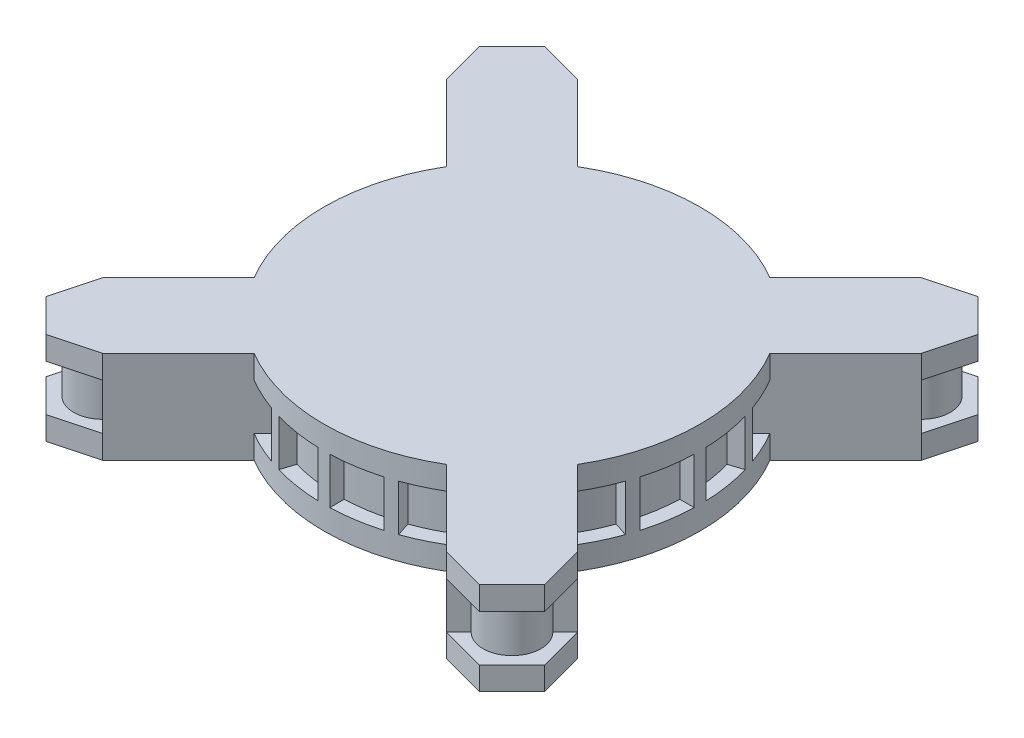
SolidWorks part; units mm, degrees
ref_plane "Front Plane" through (0, 0, 0) normal (0, 0, 1) x (1, 0, 0)
ref_plane "Top Plane" through (0, 0, 0) normal (0, 1, 0) x (1, 0, 0)
ref_plane "Right Plane" through (0, 0, 0) normal (1, 0, 0) x (0, 0, -1)
ref_plane "Plane3" through (0, 4, 0) normal (0, 1, 0) x (1, 0, 0)
ref_plane "Plane4" through (0, 12, 0) normal (0, 1, 0) x (1, 0, 0)
ref_plane "Plane5" through (0, 16, 0) normal (0, 1, 0) x (1, 0, 0)
sketch "Sketch11" plane through (0, 0, 0) normal (0, 1, 0) x (1, 0, 0)
  line L0 (27.9307, -16.617) -> (41.0122, -29.6985)
  line L1 (27.9307, 16.617) -> (41.0122, 29.6985)
  line L2 (16.617, 27.9307) -> (29.6985, 41.0122)
  line L3 (16.617, -27.9307) -> (29.6985, -41.0122)
  line L4 (-16.617, -27.9307) -> (-29.6985, -41.0122)
  line L5 (-27.9307, -16.617) -> (-41.0122, -29.6985)
  line L6 (-27.9307, 16.617) -> (-41.0122, 29.6985)
  line L7 (-16.617, 27.9307) -> (-29.6985, 41.0122)
  line L8 (43.0827, -37.4259) -> (41.0122, -29.6985)
  line L9 (37.4259, -43.0827) -> (43.0827, -37.4259)
  line L13 (41.0122, 29.6985) -> (43.0827, 37.4259)
  line L14 (43.0827, 37.4259) -> (37.4259, 43.0827)
  line L15 (37.4259, 43.0827) -> (29.6985, 41.0122)
  line L16 (30.4564, 30.4564) -> (33.2848, 27.6279) [skipped]
  line L17 (28.6632, 37.1485) -> (27.6279, 33.2848) [skipped]
  line L18 (37.1485, 28.6632) -> (41.0122, 29.6985) [skipped]
  line L19 (29.6985, -41.0122) -> (37.4259, -43.0827)
  line L20 (-37.4259, -43.0827) -> (-29.6985, -41.0122)
  line L21 (-43.0827, -37.4259) -> (-37.4259, -43.0827)
  line L22 (-41.0122, -29.6985) -> (-43.0827, -37.4259)
  line L23 (-43.0827, 37.4259) -> (-41.0122, 29.6985)
  line L24 (-37.4259, 43.0827) -> (-43.0827, 37.4259)
  line L25 (-29.6985, 41.0122) -> (-37.4259, 43.0827)
  arc A0 (16.617, 27.9307) -> (-16.617, 27.9307) centre (0, 0) ccw
  arc A1 (-27.9307, 16.617) -> (-27.9307, -16.617) centre (0, 0) ccw
  arc A2 (-16.617, -27.9307) -> (16.617, -27.9307) centre (0, 0) ccw
  arc A3 (27.9307, -16.617) -> (27.9307, 16.617) centre (0, 0) ccw
  point P23 (0, 0)
  point P46 (0, 0)
extrude "Boss-Extrude8" add sketch "Sketch11" along normal blind 4
sketch "Sketch12" plane through (0, 4, 0) normal (0, 1, 0) x (1, 0, 0)
  line L0 (38.8909, 31.8198) -> (41.0122, 29.6985)
  line L2 (26.1019, 14.7882) -> (41.0122, 29.6985)
  line L3 (14.7882, 26.1019) -> (29.6985, 41.0122)
  line L4 (29.6985, 41.0122) -> (31.8198, 38.8909)
  line L5 (26.1019, -14.7882) -> (41.0122, -29.6985)
  line L6 (41.0122, -29.6985) -> (38.8909, -31.8198)
  line L7 (31.8198, -38.8909) -> (29.6985, -41.0122)
  line L8 (14.7882, -26.1019) -> (29.6985, -41.0122)
  line L9 (-14.7882, -26.1019) -> (-29.6985, -41.0122)
  line L10 (-29.6985, -41.0122) -> (-31.8198, -38.8909)
  line L11 (-38.8909, -31.8198) -> (-41.0122, -29.6985)
  line L12 (-26.1019, -14.7882) -> (-41.0122, -29.6985)
  line L13 (-26.1019, 14.7882) -> (-41.0122, 29.6985)
  line L14 (-41.0122, 29.6985) -> (-38.8909, 31.8198)
  line L15 (-31.8198, 38.8909) -> (-29.6985, 41.0122)
  line L16 (-14.7882, 26.1019) -> (-29.6985, 41.0122)
  line L17 (-1, 32.4846) -> (-1, 29.9833)
  line L18 (10.9894, 30.5857) -> (10.2164, 28.2068)
  line L19 (1, 32.4846) -> (1, 29.9833)
  line L20 (9.0872, 31.2037) -> (8.3143, 28.8249)
  line L25 (31.2037, 9.0872) -> (28.8249, 8.3143)
  line L26 (30.5857, 10.9894) -> (28.2068, 10.2164)
  line L27 (32.4846, -1) -> (29.9833, -1)
  line L28 (32.4846, 1) -> (29.9833, 1)
  line L29 (30.5857, -10.9894) -> (28.2068, -10.2164)
  line L30 (31.2037, -9.0872) -> (28.8249, -8.3143)
  line L35 (9.0872, -31.2037) -> (8.3143, -28.8249)
  line L36 (10.9894, -30.5857) -> (10.2164, -28.2068)
  line L37 (-1, -32.4846) -> (-1, -29.9833)
  line L38 (1, -32.4846) -> (1, -29.9833)
  line L39 (-10.9894, -30.5857) -> (-10.2164, -28.2068)
  line L40 (-9.0872, -31.2037) -> (-8.3143, -28.8249)
  line L45 (-31.2037, -9.0872) -> (-28.8249, -8.3143)
  line L46 (-30.5857, -10.9894) -> (-28.2068, -10.2164)
  line L47 (-32.4846, 1) -> (-29.9833, 1)
  line L48 (-32.4846, -1) -> (-29.9833, -1)
  line L49 (-30.5857, 10.9894) -> (-28.2068, 10.2164)
  line L50 (-31.2037, 9.0872) -> (-28.8249, 8.3143)
  line L55 (-9.0872, 31.2037) -> (-8.3143, 28.8249)
  line L56 (-10.9894, 30.5857) -> (-10.2164, 28.2068)
  line L57 (-19.4257, 28.4385) -> (-12.3592, 18.7123) [skipped]
  line L58 (-21.0438, 27.263) -> (-13.9773, 17.5367) [skipped]
  line L59 (-27.263, 21.0438) -> (-17.5367, 13.9773) [skipped]
  line L60 (-28.4385, 19.4257) -> (-18.7123, 12.3592) [skipped]
  line L61 (19.4257, 28.4385) -> (12.3592, 18.7123) [skipped]
  line L62 (21.0438, 27.263) -> (13.9773, 17.5367) [skipped]
  line L63 (27.263, 21.0438) -> (17.5367, 13.9773) [skipped]
  line L64 (28.4385, 19.4257) -> (18.7123, 12.3592) [skipped]
  line L65 (27.263, -21.0438) -> (17.5367, -13.9773) [skipped]
  line L66 (28.4385, -19.4257) -> (18.7123, -12.3592) [skipped]
  line L67 (21.0438, -27.263) -> (13.9773, -17.5367) [skipped]
  line L68 (19.4257, -28.4385) -> (12.3592, -18.7123) [skipped]
  line L69 (-19.4257, -28.4385) -> (-12.3592, -18.7123) [skipped]
  line L70 (-21.0438, -27.263) -> (-13.9773, -17.5367) [skipped]
  line L71 (-27.263, -21.0438) -> (-17.5367, -13.9773) [skipped]
  line L72 (-28.4385, -19.4257) -> (-18.7123, -12.3592) [skipped]
  arc A0 (14.7882, 26.1019) -> (10.2164, 28.2068) centre (0, 0) ccw
  arc A1 (38.8909, 31.8198) -> (31.8198, 38.8909) centre (35.3553, 35.3553) ccw
  arc A2 (31.8198, -38.8909) -> (38.8909, -31.8198) centre (35.3553, -35.3553) ccw
  arc A3 (-38.8909, -31.8198) -> (-31.8198, -38.8909) centre (-35.3553, -35.3553) ccw
  arc A4 (-31.8198, 38.8909) -> (-38.8909, 31.8198) centre (-35.3553, 35.3553) ccw
  arc A5 (-26.1019, 14.7882) -> (-28.2068, 10.2164) centre (0, 0) ccw
  arc A6 (-14.7882, -26.1019) -> (-10.2164, -28.2068) centre (0, 0) ccw
  arc A7 (26.1019, -14.7882) -> (28.2068, -10.2164) centre (0, 0) ccw
  arc A8 (-31.2037, -9.0872) -> (-30.5857, -10.9894) centre (0, 0) ccw
  arc A9 (-32.4846, 1) -> (-32.4846, -1) centre (0, 0) ccw
  arc A10 (-30.5857, 10.9894) -> (-31.2037, 9.0872) centre (0, 0) ccw
  arc A11 (-10.9894, -30.5857) -> (-9.0872, -31.2037) centre (0, 0) ccw
  arc A12 (-28.8249, 8.3143) -> (-29.9833, 1) centre (0, 0) ccw
  arc A13 (-29.9833, -1) -> (-28.8249, -8.3143) centre (0, 0) ccw
  arc A14 (-28.2068, -10.2164) -> (-26.1019, -14.7882) centre (0, 0) ccw
  arc A15 (-9.0872, 31.2037) -> (-10.9894, 30.5857) centre (0, 0) ccw
  arc A16 (1, 32.4846) -> (-1, 32.4846) centre (0, 0) ccw
  arc A17 (10.9894, 30.5857) -> (9.0872, 31.2037) centre (0, 0) ccw
  arc A18 (31.2037, 9.0872) -> (30.5857, 10.9894) centre (0, 0) ccw
  arc A19 (32.4846, -1) -> (32.4846, 1) centre (0, 0) ccw
  arc A20 (30.5857, -10.9894) -> (31.2037, -9.0872) centre (0, 0) ccw
  arc A21 (-1, -32.4846) -> (1, -32.4846) centre (0, 0) ccw
  arc A22 (9.0872, -31.2037) -> (10.9894, -30.5857) centre (0, 0) ccw
  arc A23 (10.2164, -28.2068) -> (14.7882, -26.1019) centre (0, 0) ccw
  arc A24 (-8.3143, -28.8249) -> (-1, -29.9833) centre (0, 0) ccw
  arc A25 (28.8249, -8.3143) -> (29.9833, -1) centre (0, 0) ccw
  arc A26 (29.9833, 1) -> (28.8249, 8.3143) centre (0, 0) ccw
  arc A27 (28.2068, 10.2164) -> (26.1019, 14.7882) centre (0, 0) ccw
  arc A28 (-10.2164, 28.2068) -> (-14.7882, 26.1019) centre (0, 0) ccw
  arc A29 (-1, 29.9833) -> (-8.3143, 28.8249) centre (0, 0) ccw
  arc A30 (8.3143, 28.8249) -> (1, 29.9833) centre (0, 0) ccw
  arc A31 (1, -29.9833) -> (8.3143, -28.8249) centre (0, 0) ccw
  point P35 (0, 0)
  point P115 (0, 0)
  dimension "D1" = 20
  dimension "D2" = 4
extrude "Boss-Extrude10" add sketch "Sketch12" along normal blind 8
sketch "Sketch13" plane through (0, 12, 0) normal (0, 1, 0) x (1, 0, 0)
  line L0 (27.9307, -16.617) -> (41.0122, -29.6985)
  line L1 (43.0827, -37.4259) -> (41.0122, -29.6985)
  line L2 (27.9307, 16.617) -> (41.0122, 29.6985)
  line L3 (16.617, 27.9307) -> (29.6985, 41.0122)
  line L4 (37.4259, -43.0827) -> (43.0827, -37.4259)
  line L5 (41.0122, 29.6985) -> (43.0827, 37.4259)
  line L6 (43.0827, 37.4259) -> (37.4259, 43.0827)
  line L7 (37.4259, 43.0827) -> (29.6985, 41.0122)
  line L11 (27.6279, 33.2848) -> (30.4564, 30.4564) [skipped]
  line L12 (37.1485, 28.6632) -> (41.0122, 29.6985) [skipped]
  line L13 (29.6985, 41.0122) -> (28.6632, 37.1485) [skipped]
  line L14 (29.6985, -41.0122) -> (37.4259, -43.0827)
  line L15 (16.617, -27.9307) -> (29.6985, -41.0122)
  line L16 (-16.617, -27.9307) -> (-29.6985, -41.0122)
  line L17 (-37.4259, -43.0827) -> (-29.6985, -41.0122)
  line L18 (-43.0827, -37.4259) -> (-37.4259, -43.0827)
  line L19 (-41.0122, -29.6985) -> (-43.0827, -37.4259)
  line L20 (-27.9307, -16.617) -> (-41.0122, -29.6985)
  line L21 (-27.9307, 16.617) -> (-41.0122, 29.6985)
  line L22 (-43.0827, 37.4259) -> (-41.0122, 29.6985)
  line L23 (-37.4259, 43.0827) -> (-43.0827, 37.4259)
  line L24 (-29.6985, 41.0122) -> (-37.4259, 43.0827)
  line L25 (-16.617, 27.9307) -> (-29.6985, 41.0122)
  arc A0 (16.617, 27.9307) -> (-16.617, 27.9307) centre (0, 0) ccw
  arc A1 (-27.9307, 16.617) -> (-27.9307, -16.617) centre (0, 0) ccw
  arc A2 (-16.617, -27.9307) -> (16.617, -27.9307) centre (0, 0) ccw
  arc A3 (27.9307, -16.617) -> (27.9307, 16.617) centre (0, 0) ccw
  point P37 (0, 0)
extrude "Boss-Extrude11" add sketch "Sketch13" along normal blind 4
sketch "Sketch14" plane through (0, 16, 0) normal (0, 1, 0) x (1, 0, 0)
  line L1 (-10.2, -10.2) -> (10.2, -10.2)
  line L2 (-10.2, -10.2) -> (-10.2, 10.2)
  line L3 (-10.2, 10.2) -> (10.2, 10.2)
  line L4 (10.2, -10.2) -> (10.2, 10.2)
  line L5 (-10.2, -10.2) -> (10.2, 10.2) construction
  line L6 (-10.2, 10.2) -> (10.2, -10.2) construction
  circle A1 centre (-35.3553, 35.3553) radius 2.7
  circle A2 centre (35.3553, 35.3553) radius 2.7
  circle A3 centre (35.3553, -35.3553) radius 2.7
  circle A4 centre (-35.3553, -35.3553) radius 2.7
  point P1 (0, 0)
  point P17 (0, 0)
